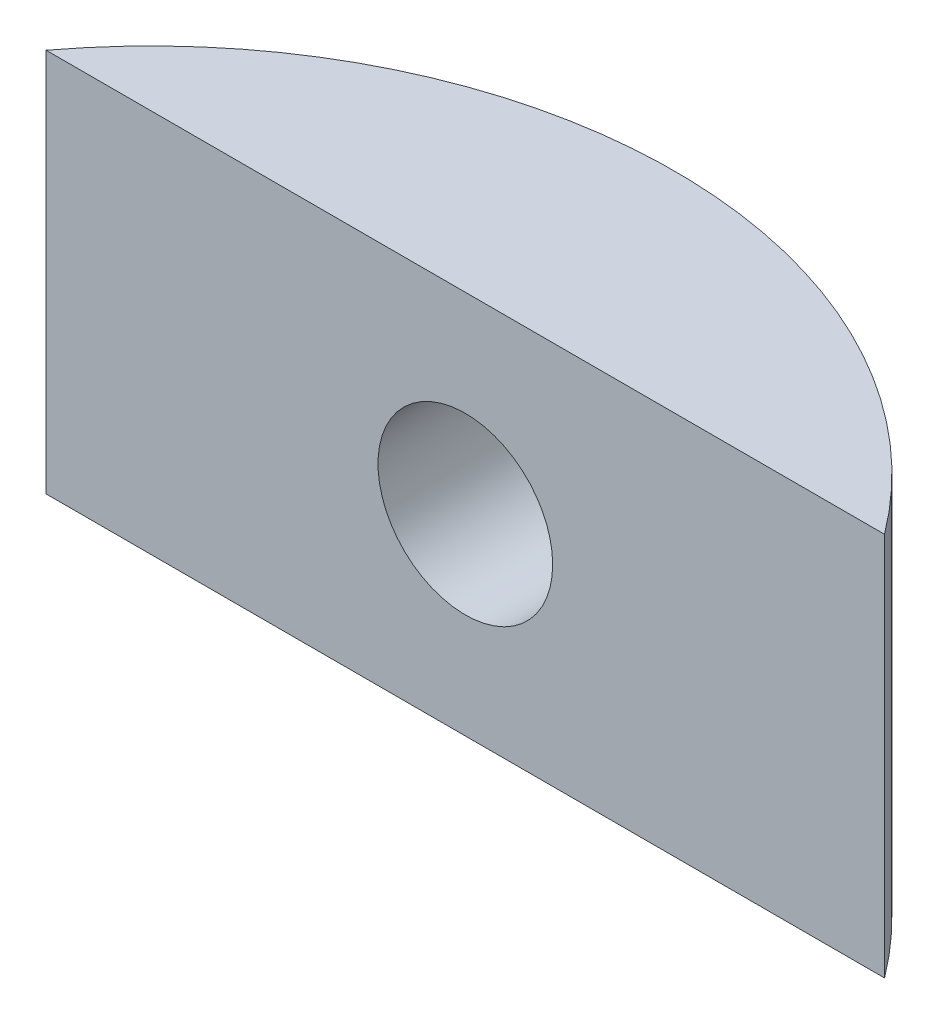
SolidWorks part; units mm, degrees
ref_plane "前视基准面" through (0, 0, 0) normal (0, 0, 1) x (1, 0, 0)
ref_plane "上视基准面" through (0, 0, 0) normal (0, 1, 0) x (1, 0, 0)
ref_plane "右视基准面" through (0, 0, 0) normal (1, 0, 0) x (0, 0, -1)
other "Configuration Table"
sketch "草图2" plane through (0, 0, 0) normal (0, 1, 0) x (1, 0, 0)
  line L0 (0, 0) -> (0, 9)
  line L1 (0, 9) -> (-12, 9)
  line L2 (-12, 9) -> (12, 9)
  circle A0 centre (0, 0) radius 15
  dimension "D1" = 30
  dimension "D2" = 9
extrude "凸台-拉伸1" add sketch "草图2" along normal blind 11 contours L2 A0 L1
sketch "草图3" plane through (0, 0, -9) normal (0, 0, 1) x (1, 0, 0)
  line L0 (0, 0) -> (0, 11)
  line L1 (-12, 11) -> (12, 11) construction
  circle A0 centre (0, 5.5) radius 2.5
  dimension "D1" = 5
extrude "切除-拉伸2" cut sketch "草图3" against normal blind 5 contours L0 A0 | L0 A0
